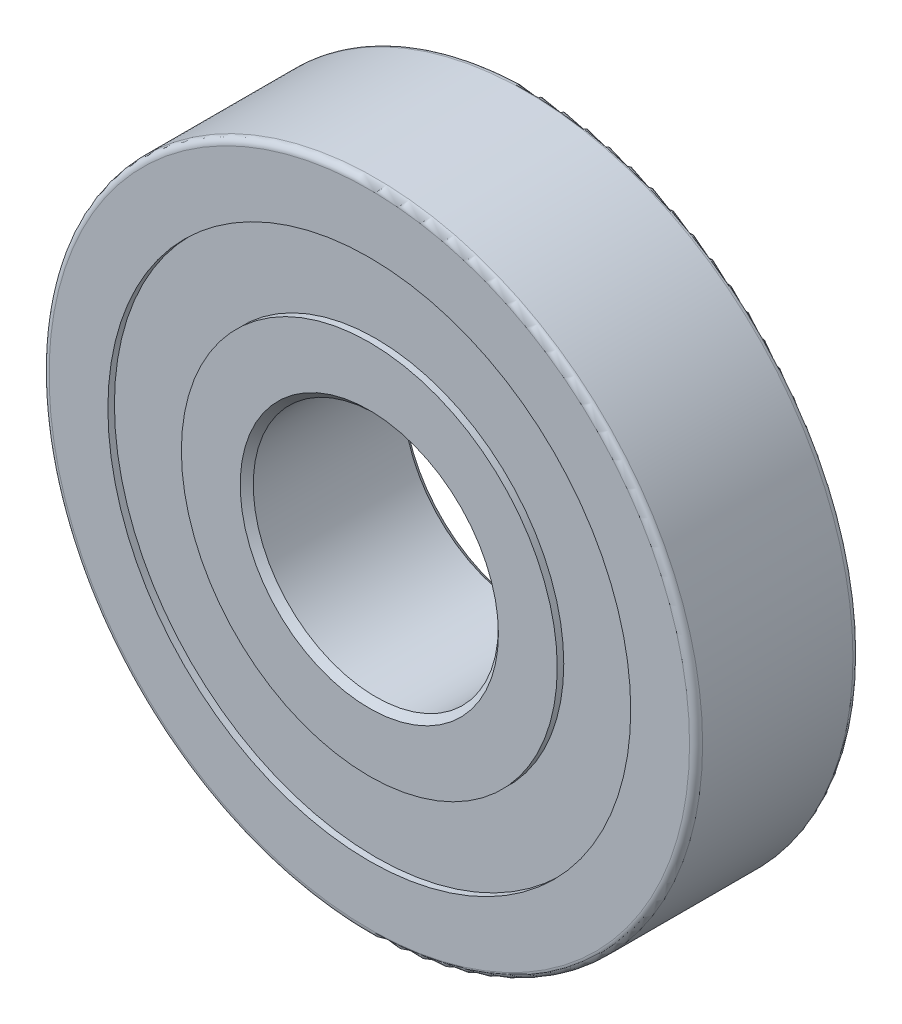
SolidWorks part; units mm, degrees
material "Chrome Stainless Steel"
ref_plane "Front Plane" through (0, 0, 0) normal (0, 0, 1) x (1, 0, 0)
ref_plane "Top Plane" through (0, 0, 0) normal (0, 1, 0) x (1, 0, 0)
ref_plane "Right Plane" through (0, 0, 0) normal (1, 0, 0) x (0, 0, -1)
sketch "Sketch1" plane through (0, 0, 0) normal (0, 0, 1) x (1, 0, 0)
  circle A0 centre (0, 0) radius 6.35
  circle A1 centre (0, 0) radius 2.382
  circle A2 centre (0, 0) radius 5.08
  circle A3 centre (0, 0) radius 3.652
  dimension "D1" = 12.7
  dimension "D2" = 4.764
  dimension "D3" = 1.27
  dimension "D4" = 1.27
extrude "Boss-Extrude1" add sketch "Sketch1" along normal mid plane 3.175 contours A0 A2 | A3 A1
sketch "Sketch2" plane through (0, 0, 0) normal (0, 0, 1) x (1, 0, 0)
  circle A0 centre (0, 0) radius 6.35
  circle A1 centre (0, 0) radius 5.08
  circle A2 centre (0, 0) radius 5.08
  circle A3 centre (0, 0) radius 6.35 construction
  circle A4 centre (0, 0) radius 3.652 construction
  circle A5 centre (0, 0) radius 3.652
extrude "Boss-Extrude2" add sketch "Sketch2" along normal mid plane 2.921
fillet "Fillet1" radius 0.127 2 edges at (6.35, 0, -1.5875) (6.35, 0, 1.5875)
chamfer "Chamfer1" distance 0.127 angle 45 2 edges at (2.382, 0, 1.5875) (2.382, 0, -1.5875)
